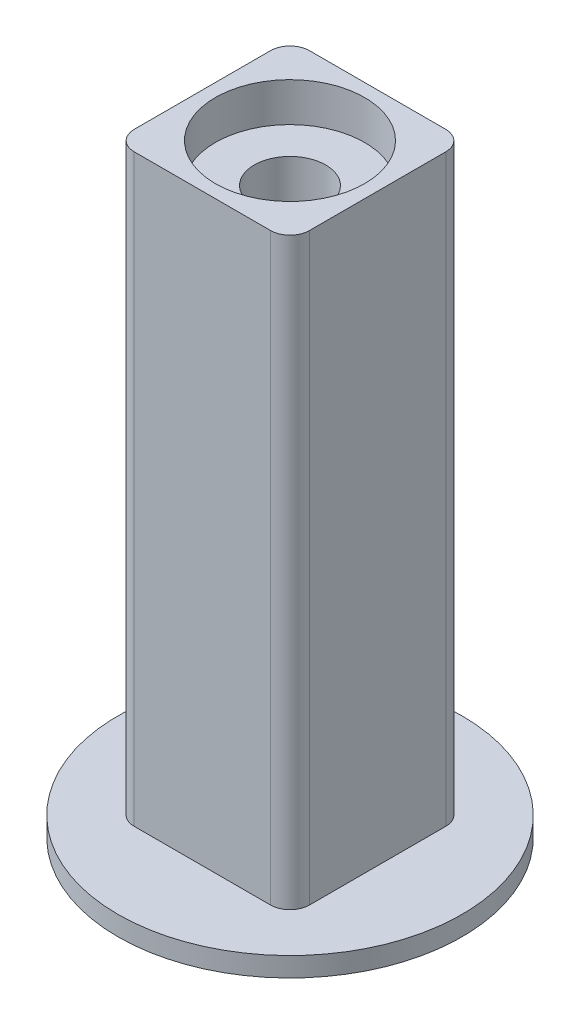
SolidWorks part; units mm, degrees
ref_plane "Front Plane" through (0, 0, 0) normal (0, 0, 1) x (1, 0, 0)
ref_plane "Top Plane" through (0, 0, 0) normal (0, 1, 0) x (1, 0, 0)
ref_plane "Right Plane" through (0, 0, 0) normal (1, 0, 0) x (0, 0, -1)
sketch "Sketch1" plane through (0, 0, 0) normal (0, 1, 0) x (1, 0, 0)
  circle A0 centre (0, 0) radius 26.5
  dimension "D1" = 53
extrude "Boss-Extrude1" add sketch "Sketch1" along normal blind 3
sketch "Sketch10" plane through (0, 3, 0) normal (0, 1, 0) x (1, 0, 0)
  line L1 (-13.5, 13.5) -> (13.5, 13.5)
  line L2 (-13.5, 13.5) -> (-13.5, -13.5)
  line L3 (-13.5, -13.5) -> (13.5, -13.5)
  line L4 (13.5, 13.5) -> (13.5, -13.5)
  line L5 (-13.5, 13.5) -> (13.5, -13.5) construction
  line L6 (-13.5, -13.5) -> (13.5, 13.5) construction
  point P0 (0, 0)
  dimension "D1" = 27
  dimension "D2" = 27
extrude "Boss-Extrude6" add sketch "Sketch10" along normal blind 90
sketch "Sketch11" plane through (0, 93, 0) normal (0, 1, 0) x (1, 0, 0)
  circle A0 centre (0, 0) radius 5.5
  dimension "D1" = 11
extrude "Cut-Extrude3" cut sketch "Sketch11" against normal blind 90
sketch "Sketch12" plane through (0, 93, 0) normal (0, 1, 0) x (1, 0, 0)
  circle A0 centre (0, 0) radius 11.5
  dimension "D1" = 23
extrude "Cut-Extrude4" cut sketch "Sketch12" against normal blind 6
fillet "Fillet2" radius 3 4 edges at (13.5, 48, -13.5) (-13.5, 48, -13.5) (-13.5, 48, 13.5) (13.5, 48, 13.5)
